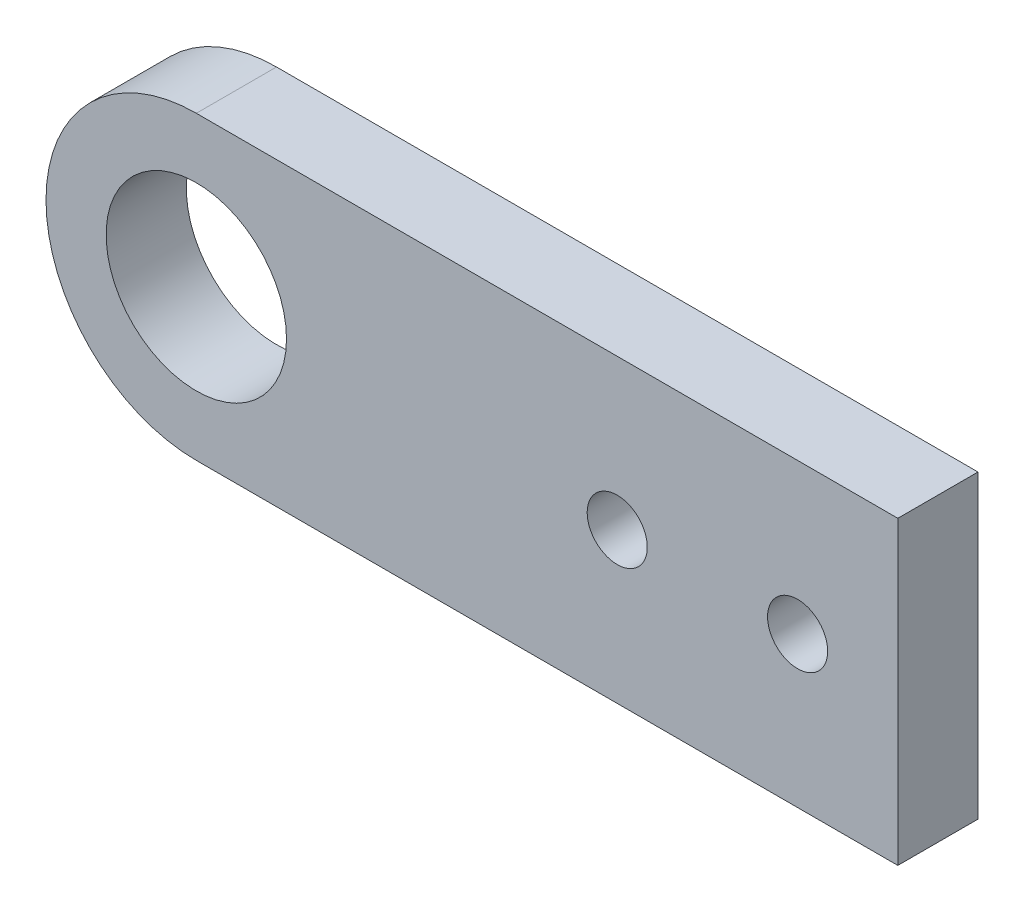
SolidWorks part; units mm, degrees
ref_plane "Front Plane" through (0, 0, 0) normal (0, 0, 1) x (1, 0, 0)
ref_plane "Top Plane" through (0, 0, 0) normal (0, 1, 0) x (1, 0, 0)
ref_plane "Right Plane" through (0, 0, 0) normal (1, 0, 0) x (0, 0, -1)
sketch "Sketch1" plane through (0, 0, 0) normal (0, 0, 1) x (1, 0, 0)
  line L0 (0, 0) -> (70, 0)
  line L1 (0, 30) -> (70, 30)
  line L2 (70, 30) -> (70, 0)
  arc A0 (0, 30) -> (0, 0) centre (0, 15) ccw
  dimension "D2" = 15
  dimension "D1" = 30
  dimension "D3" = 70
extrude "Boss-Extrude1" add sketch "Sketch1" along normal blind 8 contours L1 L2 L0 A0
sketch "Sketch2" plane through (0, 0, 8) normal (0, 0, 1) x (1, 0, 0)
  circle A0 centre (0, 15) radius 9
  arc A1 (0, 30) -> (0, 0) centre (0, 15) ccw construction
  dimension "D1" = 18
extrude "Cut-Extrude1" cut sketch "Sketch2" against normal up to next
sketch "Sketch3" plane through (0, 0, 0) normal (0, 0, -1) x (-1, 0, 0)
  line L0 (-70, 30) -> (-70, 0) construction
  line L1 (0, 0) -> (-70, 0) construction
  point P0 (-42, 15)
  point P2 (-60, 15)
  dimension "D1" = 10
  dimension "D2" = 18
  dimension "D3" = 15
hole_wizard "Ø6.0mm Dowel Hole1" positions "Sketch3" profile "Sketch4" hole size "Ø6.0" standard "ANSI Metric" end condition through all
sketch "Sketch4" plane through (42, 15, 0) normal (1, 0, 0) x (0, 1, 0)
  line L0 (0, 0) -> (0, 8)
  line L1 (0, 8) -> (3, 8)
  line L2 (3, 8) -> (3, 0)
  line L5 (3, 0) -> (0, 0)
  line L11 (0, -6.35) -> (0, 107.95) construction
  dimension "Thru Hole Dia." = 6
  dimension "Thru Hole Depth" = 8
